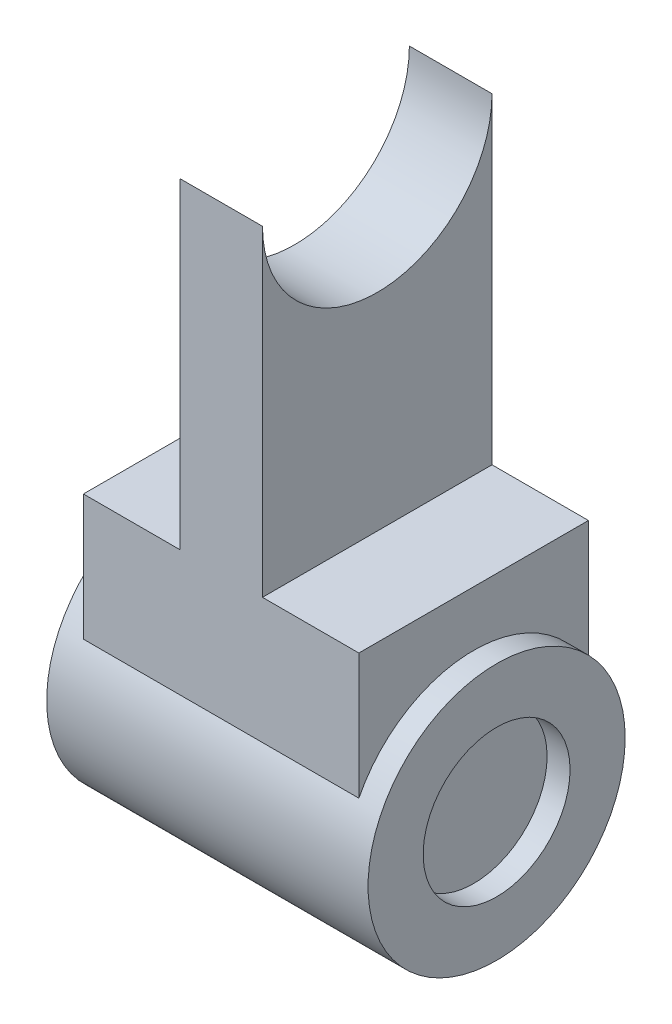
SolidWorks part; units mm, degrees
ref_plane "Front Plane" through (0, 0, 0) normal (0, 0, 1) x (1, 0, 0)
ref_plane "Top Plane" through (0, 0, 0) normal (0, 1, 0) x (1, 0, 0)
ref_plane "Right Plane" through (0, 0, 0) normal (1, 0, 0) x (0, 0, -1)
sketch "Sketch1" plane through (0, 0, 0) normal (1, 0, 0) x (0, 0, -1)
  circle A0 centre (0, 0) radius 16
  circle A1 centre (0, 0) radius 28
  dimension "D1" = 32
  dimension "D2" = 56
extrude "Boss-Extrude1" add sketch "Sketch1" along normal mid plane 70
sketch "Sketch2" plane through (0, 0, 0) normal (1, 0, 0) x (0, 0, -1)
  line L0 (0, 0) -> (44.9541, 0) construction
  line L1 (0, 0) -> (0, 40) construction
  line L2 (-25, 40) -> (25, 40)
  line L3 (-25, 40) -> (-25, 12.6095)
  line L4 (25, 40) -> (25, 12.6095)
  circle A0 centre (0, 0) radius 28 construction
  circle A2 centre (0, 0) radius 28
  arc A3 (-25, 12.6095) -> (25, 12.6095) centre (0, 0) ccw
  point P7 (0, 40)
  dimension "D1" = 50
  dimension "D2" = 40
  dimension "D3" = 0
extrude "Boss-Extrude2" add sketch "Sketch2" along normal mid plane 60
sketch "Sketch3" plane through (0, 0, 0) normal (1, 0, 0) x (0, 0, -1)
  line L0 (-25, 40) -> (-25, 110)
  line L1 (25, 40) -> (25, 110)
  line L5 (25, 12.6095) -> (25, 40)
  line L6 (25, 40) -> (-25, 40)
  line L7 (-25, 40) -> (-25, 12.6095)
  line L8 (25, 12.6095) -> (25, 40)
  line L10 (-25, 40) -> (-25, 12.6095)
  arc A1 (-25, 110) -> (25, 110) centre (0, 110) ccw
  arc A3 (25, 12.6095) -> (-25, 12.6095) centre (0, 0) ccw
  arc A4 (25, 12.6095) -> (-25, 12.6095) centre (0, 0) ccw
  dimension "D2" = 0
  dimension "D3" = 50
  dimension "D1" = 110
extrude "Boss-Extrude3" add sketch "Sketch3" along normal mid plane 18
sketch "Sketch6" plane through (0, 0, 0) normal (1, 0, 0) x (0, 0, -1)
  circle A0 centre (0, 110) radius 25
  circle A1 centre (0, 110) radius 12.3766
